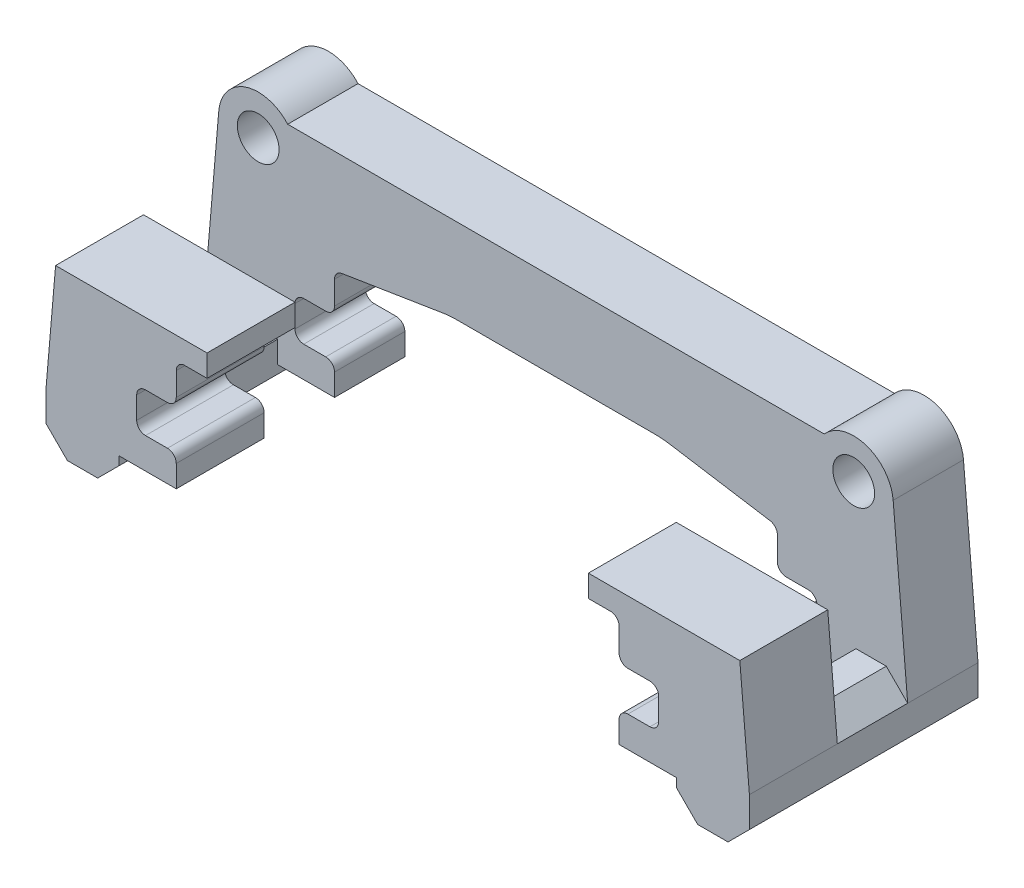
SolidWorks part; units mm, degrees
ref_plane "Front Plane" through (0, 0, 0) normal (0, 0, 1) x (1, 0, 0)
ref_plane "Top Plane" through (0, 0, 0) normal (0, 1, 0) x (1, 0, 0)
ref_plane "Right Plane" through (0, 0, 0) normal (1, 0, 0) x (0, 0, -1)
sketch "Sketch1" plane through (0, 0, 0) normal (0, 0, 1) x (1, 0, 0)
  line L0 (-80, 0) -> (80, 0) construction
  line L1 (0, 92.9069) -> (0, -13.0142) construction
  line L10 (-80, 3.4442) -> (-76.6991, 41.7722)
  line L11 (-63.3702, -3.4442) -> (-63.3702, 3.4442) construction
  line L12 (-63.3702, 3.4442) -> (-68.2409, 8.3149) construction
  line L13 (-68.2409, 8.3149) -> (-75.1292, 8.3149) construction
  line L14 (-75.1292, 8.3149) -> (-80, 3.4442) construction
  line L15 (-80, 3.4442) -> (-80, -3.4442)
  line L16 (-80, -3.4442) -> (-75.1292, -8.3149)
  line L17 (-75.1292, -8.3149) -> (-68.2409, -8.3149)
  line L18 (-68.2409, -8.3149) -> (-63.3702, -3.4442)
  line L19 (-75.9905, 50) -> (0, 50) construction
  line L20 (-80, 3.4442) -> (-75.9905, 50) construction
  line L21 (-61.0241, 47) -> (61.0241, 47)
  line L22 (-73.2377, 47) -> (0, 47) construction
  line L23 (-77.0111, 3.1867) -> (-73.2377, 47) construction
  line L24 (-63.3702, 0) -> (63.3702, 0) construction
  line L25 (75.9905, 50) -> (0, 50) construction
  line L26 (68.2409, -8.3149) -> (63.3702, -3.4442)
  line L27 (75.1292, -8.3149) -> (68.2409, -8.3149)
  line L28 (80, -3.4442) -> (75.1292, -8.3149)
  line L29 (80, 3.4442) -> (80, -3.4442)
  line L30 (75.1292, 8.3149) -> (80, 3.4442) construction
  line L31 (68.2409, 8.3149) -> (75.1292, 8.3149) construction
  line L32 (63.3702, 3.4442) -> (68.2409, 8.3149) construction
  line L33 (63.3702, -3.4442) -> (63.3702, 3.4442) construction
  line L34 (80, 3.4442) -> (76.6991, 41.7722)
  line L35 (-63.3702, -1.5) -> (63.3702, -1.5)
  line L36 (-63.3702, -1.5) -> (-63.3702, -3.4442)
  line L37 (63.3702, -1.5) -> (63.3702, -3.4442)
  circle A0 centre (-71.6851, 0) radius 9 construction
  circle A2 centre (-71.6851, 0) radius 5.115
  arc A3 (-61.0241, 47) -> (-76.6991, 41.7722) centre (-67.7323, 41) ccw
  circle A4 centre (-67.7323, 41) radius 4.75
  circle A5 centre (71.6851, 0) radius 9 construction
  circle A6 centre (67.7323, 41) radius 4.75
  arc A7 (61.0241, 47) -> (76.6991, 41.7722) centre (67.7323, 41) cw
  circle A8 centre (71.6851, 0) radius 5.115
  point P2 (0, 0)
  point P4 (-80, 0)
  point P18 (0, 50)
  point P39 (0, 0)
  dimension "D2" = 18
  dimension "D3" = 10.23
  dimension "D4" = 50
  dimension "D5" = 18
  dimension "D6" = 9.5
  dimension "D1" = 160
  dimension "D7" = 3
  dimension "D8" = 1.5
extrude "Boss-Extrude1" add sketch "Sketch1" along normal blind 16
sketch "Sketch2" plane through (0, 0, 0) normal (0, 0, -1) x (-1, 0, 0)
  line L0 (0, 58.0008) -> (0, -27.0682) construction
  line L1 (-50.3702, -1.5) -> (-50.3702, 5.5) construction
  line L2 (-61.0241, 47) -> (61.0241, 47) construction
  line L3 (63.3702, -1.5) -> (-63.3702, -1.5) construction
  line L4 (-63.3702, -1.5) -> (-63.3702, -3.4442) construction
  line L5 (-50.3702, 3.5) -> (-50.3702, -2.5)
  line L6 (-52.3702, 5.5) -> (-57.3702, 5.5)
  line L8 (-52.3702, 14.5) -> (-57.3702, 14.5)
  line L9 (-59.3702, 7.5) -> (-59.3702, 12.5)
  line L10 (-50.3702, 16.5) -> (-50.3702, 21.7956)
  line L11 (-50.3702, 29.7118) -> (54.6448, 29.7118) construction
  line L12 (-22.5495, 27.7118) -> (22.5495, 27.7118)
  line L13 (-48.6873, 23.7703) -> (-25.7209, 27.4587)
  line L14 (-50.3702, 27.7118) -> (54.6448, 27.7118) construction
  line L15 (48.6873, 23.7703) -> (25.7209, 27.4587)
  line L16 (50.3702, 16.5) -> (50.3702, 21.7956)
  line L17 (59.3702, 7.5) -> (59.3702, 12.5)
  line L18 (52.3702, 14.5) -> (57.3702, 14.5)
  line L19 (-50.3702, -2.5) -> (50.3702, -2.5)
  line L20 (52.3702, 5.5) -> (57.3702, 5.5)
  line L21 (50.3702, 3.5) -> (50.3702, -2.5)
  line L22 (-50.3702, 14.5) -> (-50.3702, 47) construction
  circle A0 centre (0, 0) radius 32.8 construction
  circle A1 centre (-71.6851, 0) radius 5.115 construction
  circle A2 centre (-71.6851, 0) radius 5.115 construction
  arc A3 (25.7209, 27.4587) -> (22.5495, 27.7118) centre (22.5495, 7.7118) ccw
  arc A4 (-25.7209, 27.4587) -> (-22.5495, 27.7118) centre (-22.5495, 7.7118) cw
  arc A5 (59.3702, 12.5) -> (57.3702, 14.5) centre (57.3702, 12.5) ccw
  arc A6 (59.3702, 7.5) -> (57.3702, 5.5) centre (57.3702, 7.5) cw
  arc A7 (50.3702, 3.5) -> (52.3702, 5.5) centre (52.3702, 3.5) cw
  arc A8 (50.3702, 16.5) -> (52.3702, 14.5) centre (52.3702, 16.5) ccw
  arc A9 (48.6873, 23.7703) -> (50.3702, 21.7956) centre (48.3702, 21.7956) cw
  arc A10 (-50.3702, 21.7956) -> (-48.6873, 23.7703) centre (-48.3702, 21.7956) cw
  arc A11 (-52.3702, 5.5) -> (-50.3702, 3.5) centre (-52.3702, 3.5) cw
  arc A12 (-50.3702, 16.5) -> (-52.3702, 14.5) centre (-52.3702, 16.5) cw
  arc A13 (-57.3702, 14.5) -> (-59.3702, 12.5) centre (-57.3702, 12.5) ccw
  arc A14 (-57.3702, 5.5) -> (-59.3702, 7.5) centre (-57.3702, 7.5) cw
  point P28 (0, 27.7118)
  point P37 (24.1453, 27.7118)
  point P40 (-24.1453, 27.7118)
  point P42 (59.3702, 14.5)
  point P45 (59.3702, 5.5)
  point P48 (50.3702, 5.5)
  point P51 (50.3702, 14.5)
  point P54 (50.3702, 23.5)
  point P57 (-50.3702, 23.5)
  point P66 (-59.3702, 14.5)
  point P69 (-59.3702, 5.5)
  dimension "D1" = 65.6
  dimension "D2" = 20
  dimension "D9" = 2
  dimension "9" = 13
  dimension "D3" = 9
  dimension "D4" = 9
  dimension "D5" = 7
  dimension "D6" = 1
  dimension "D7" = 9
  dimension "D8" = 2
extrude "Cut-Extrude1" cut sketch "Sketch2" against normal through all
sketch "Sketch3" plane through (0, 0, 16) normal (0, 0, 1) x (1, 0, 0)
  line L0 (-80, 3.4442) -> (-80, -3.4442) construction
  line L1 (-80, -3.4442) -> (-75.1292, -8.3149) construction
  line L2 (-75.1292, -8.3149) -> (-68.2409, -8.3149) construction
  line L3 (-68.2409, -8.3149) -> (-63.3702, -3.4442) construction
  line L4 (-63.3702, -3.4442) -> (-63.3702, 3.4442) construction
  line L5 (-63.3702, 3.4442) -> (-68.2409, 8.3149) construction
  line L6 (-68.2409, 8.3149) -> (-75.1292, 8.3149) construction
  line L7 (-75.1292, 8.3149) -> (-80, 3.4442) construction
  line L8 (-80, 3.4442) -> (-80, -3.4442)
  line L9 (-80, -3.4442) -> (-75.1292, -8.3149)
  line L10 (-75.1292, -8.3149) -> (-68.2409, -8.3149)
  line L11 (-68.2409, -8.3149) -> (-63.3702, -3.4442)
  line L12 (-63.3702, -3.4442) -> (-63.3702, 3.4442)
  line L13 (-63.3702, 3.4442) -> (-68.2409, 8.3149)
  line L14 (-68.2409, 8.3149) -> (-75.1292, 8.3149)
  line L15 (-75.1292, 8.3149) -> (-80, 3.4442)
  circle A0 centre (-71.6851, 0) radius 9 construction
  circle A1 centre (-71.6851, 0) radius 9 construction
  circle A2 centre (-71.6851, 0) radius 5.115 construction
  circle A3 centre (-71.6851, 0) radius 5.115
extrude "Boss-Extrude2" add sketch "Sketch3" along normal blind 16
mirror "Mirror1" about plane through (0, 0, 0) normal (1, 0, 0) of "Boss-Extrude2"
ref_plane "Plane1" through (0, 0, 32) normal (0, 0, 1) x (1, 0, 0)
sketch "Sketch4" plane through (0, 0, 32) normal (0, 0, 1) x (1, 0, 0)
  line L0 (-77.8188, 28.7703) -> (-43.3702, 28.7703)
  line L1 (-48.6873, 23.7703) -> (-43.3702, 23.7703)
  line L2 (-77.8188, 23.7703) -> (-43.3702, 23.7703) construction
  line L3 (-43.3702, 28.7703) -> (-43.3702, 23.7703)
  line L14 (52.3702, 5.5) -> (57.3702, 5.5)
  line L15 (50.3702, -2.5) -> (50.3702, 3.5)
  line L16 (-50.3702, -2.5) -> (50.3702, -2.5)
  line L17 (-50.3702, 3.5) -> (-50.3702, -2.5)
  line L18 (-57.3702, 5.5) -> (-52.3702, 5.5)
  line L19 (-59.3702, 12.5) -> (-59.3702, 7.5)
  line L20 (-52.3702, 14.5) -> (-57.3702, 14.5)
  line L21 (-50.3702, 21.7956) -> (-50.3702, 16.5)
  line L22 (-25.7209, 27.4587) -> (-48.6873, 23.7703)
  line L23 (22.5495, 27.7118) -> (-22.5495, 27.7118)
  line L24 (48.6873, 23.7703) -> (25.7209, 27.4587)
  line L25 (50.3702, 16.5) -> (50.3702, 21.7956)
  line L26 (57.3702, 14.5) -> (52.3702, 14.5)
  line L27 (59.3702, 7.5) -> (59.3702, 12.5)
  line L31 (-50.3702, 3.5) -> (-50.3702, -1.5)
  line L32 (-57.3702, 5.5) -> (-52.3702, 5.5)
  line L33 (-59.3702, 12.5) -> (-59.3702, 7.5)
  line L34 (-52.3702, 14.5) -> (-57.3702, 14.5)
  line L35 (-50.3702, 21.7956) -> (-50.3702, 16.5)
  line L42 (-63.3702, -1.5) -> (63.3702, -1.5)
  line L43 (-63.3702, -3.4442) -> (-63.3702, -1.5)
  line L44 (-68.2409, -8.3149) -> (-63.3702, -3.4442)
  line L45 (-75.1292, -8.3149) -> (-68.2409, -8.3149)
  line L46 (-80, -3.4442) -> (-75.1292, -8.3149)
  line L47 (-80, 3.4442) -> (-80, -3.4442)
  line L48 (-76.6991, 41.7722) -> (-80, 3.4442)
  line L49 (61.0241, 47) -> (-61.0241, 47)
  line L50 (80, 3.4442) -> (76.6991, 41.7722)
  line L51 (80, -3.4442) -> (80, 3.4442)
  line L52 (75.1292, -8.3149) -> (80, -3.4442)
  line L53 (68.2409, -8.3149) -> (75.1292, -8.3149)
  line L54 (63.3702, -3.4442) -> (68.2409, -8.3149)
  line L55 (63.3702, -1.5) -> (63.3702, -3.4442)
  line L56 (-63.3702, -1.5) -> (-50.3702, -1.5)
  line L57 (-63.3702, -3.4442) -> (-63.3702, -1.5)
  line L58 (-68.2409, -8.3149) -> (-63.3702, -3.4442)
  line L59 (-75.1292, -8.3149) -> (-68.2409, -8.3149)
  line L60 (-80, -3.4442) -> (-75.1292, -8.3149)
  line L61 (-80, 3.4442) -> (-80, -3.4442)
  line L62 (-77.8188, 28.7703) -> (-80, 3.4442)
  arc A10 (-61.0241, 47) -> (-76.6991, 41.7722) centre (-67.7323, 41) ccw
  arc A11 (76.6991, 41.7722) -> (61.0241, 47) centre (67.7323, 41) ccw
  arc A12 (52.3702, 5.5) -> (50.3702, 3.5) centre (52.3702, 3.5) ccw
  arc A13 (-50.3702, 3.5) -> (-52.3702, 5.5) centre (-52.3702, 3.5) ccw
  arc A14 (-59.3702, 7.5) -> (-57.3702, 5.5) centre (-57.3702, 7.5) ccw
  arc A15 (-57.3702, 14.5) -> (-59.3702, 12.5) centre (-57.3702, 12.5) ccw
  arc A16 (-52.3702, 14.5) -> (-50.3702, 16.5) centre (-52.3702, 16.5) ccw
  arc A17 (-48.6873, 23.7703) -> (-50.3702, 21.7956) centre (-48.3702, 21.7956) ccw
  arc A18 (-22.5495, 27.7118) -> (-25.7209, 27.4587) centre (-22.5495, 7.7118) ccw
  arc A19 (25.7209, 27.4587) -> (22.5495, 27.7118) centre (22.5495, 7.7118) ccw
  arc A20 (50.3702, 21.7956) -> (48.6873, 23.7703) centre (48.3702, 21.7956) ccw
  arc A21 (50.3702, 16.5) -> (52.3702, 14.5) centre (52.3702, 16.5) ccw
  arc A22 (59.3702, 12.5) -> (57.3702, 14.5) centre (57.3702, 12.5) ccw
  arc A23 (57.3702, 5.5) -> (59.3702, 7.5) centre (57.3702, 7.5) ccw
  arc A25 (-50.3702, 3.5) -> (-52.3702, 5.5) centre (-52.3702, 3.5) ccw
  arc A26 (-59.3702, 7.5) -> (-57.3702, 5.5) centre (-57.3702, 7.5) ccw
  arc A27 (-57.3702, 14.5) -> (-59.3702, 12.5) centre (-57.3702, 12.5) ccw
  arc A28 (-52.3702, 14.5) -> (-50.3702, 16.5) centre (-52.3702, 16.5) ccw
  arc A29 (-48.6873, 23.7703) -> (-50.3702, 21.7956) centre (-48.3702, 21.7956) ccw
  dimension "D7" = 5
  dimension "D1" = 0
  dimension "D6" = 0
  dimension "D9" = 5
extrude "Boss-Extrude3" add sketch "Sketch4" along normal blind 20
mirror "Mirror2" about plane through (0, 0, 0) normal (1, 0, 0) of "Boss-Extrude3"
equation "\"disk_thickness\"=10"
equation "\"D1@Boss-Extrude1\"=16"
